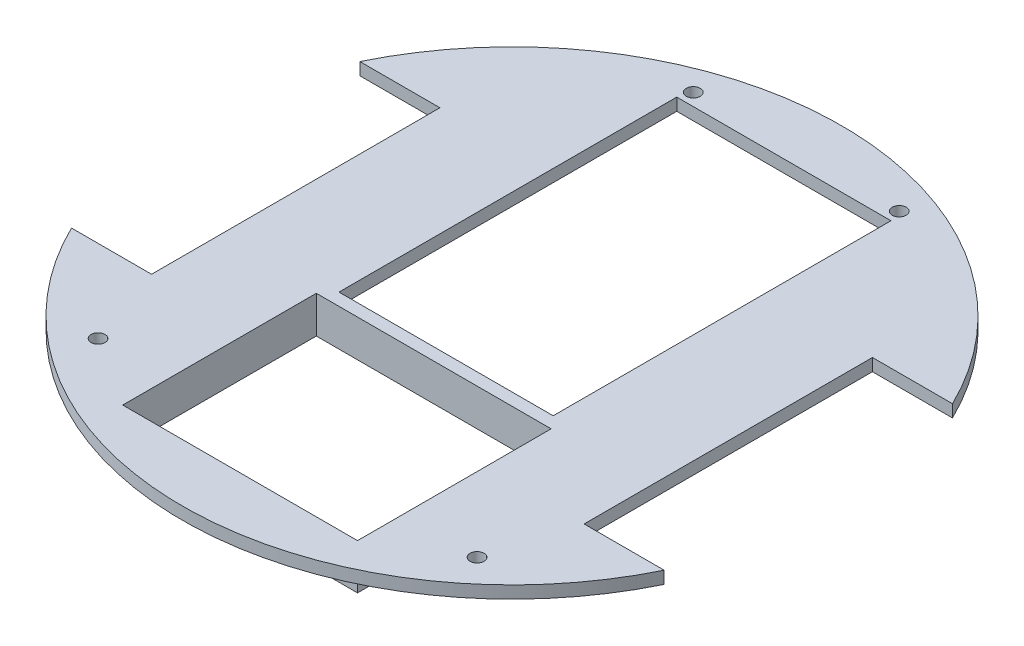
SolidWorks part; units mm, degrees
ref_plane "Plan de face" through (0, 0, 0) normal (0, 0, 1) x (1, 0, 0)
ref_plane "Plan de dessus" through (0, 0, 0) normal (0, 1, 0) x (1, 0, 0)
ref_plane "Plan de droite" through (0, 0, 0) normal (1, 0, 0) x (0, 0, -1)
sketch "Esquisse1" plane through (0, 0, 0) normal (0, 1, 0) x (1, 0, 0)
  circle A0 centre (0, 0) radius 80
  dimension "D1" = 160
extrude "Boss.-Extru.1" add sketch "Esquisse1" along normal blind 3
sketch "Esquisse2" plane through (0, 3, 0) normal (0, 1, 0) x (1, 0, 0)
  line L0 (0, -91.4679) -> (0, 85.097) construction
  line L1 (-107.5, -35) -> (-52.5, -35)
  line L2 (-107.5, -35) -> (-107.5, 35)
  line L3 (-107.5, 35) -> (-52.5, 35)
  line L4 (-52.5, -35) -> (-52.5, 35)
  line L5 (-107.5, -35) -> (-52.5, 35) construction
  line L6 (-107.5, 35) -> (-52.5, -35) construction
  line L7 (107.5, -35) -> (52.5, -35)
  line L8 (52.5, -35) -> (52.5, 35)
  line L9 (107.5, 35) -> (52.5, 35)
  line L10 (107.5, -35) -> (107.5, 35)
  circle A0 centre (0, 0) radius 80 construction
  point P0 (-80, 0)
  point P14 (0, 0)
  dimension "D1" = 70
  dimension "D2" = 55
extrude "Enlèv. mat.-Extru.1" cut sketch "Esquisse2" against normal through all
sketch "supports moteurs" plane through (0, 3, 0) normal (0, 1, 0) x (1, 0, 0)
  line L0 (-88.0211, 0) -> (120.7529, 0) construction
  line L1 (0, -36.8171) -> (0, 105.1916) construction
  line L2 (-48.5, -25) -> (-33.5, -25)
  line L3 (-48.5, -25) -> (-48.5, 65)
  line L4 (-48.5, 65) -> (-33.5, 65)
  line L5 (-33.5, -25) -> (-33.5, 65)
  line L6 (48.5, -25) -> (33.5, -25)
  line L7 (33.5, -25) -> (33.5, 65)
  line L8 (48.5, -25) -> (48.5, 65)
  line L9 (48.5, 65) -> (33.5, 65)
  line L10 (-52.5, -35) -> (-52.5, 35) construction
  dimension "D1" = 15
  dimension "D2" = 90
  dimension "D3" = 65
  dimension "D4" = 4
sketch "composants" plane through (0, 3, 0) normal (0, 1, 0) x (1, 0, 0)
  line L0 (0, -36.8171) -> (0, 105.1916) construction
  line L1 (-25, 65) -> (25, 65)
  line L2 (-25, 65) -> (-25, 15)
  line L3 (-25, 15) -> (25, 15)
  line L4 (25, 65) -> (25, 15)
  line L5 (13, 65) -> (13, 53) construction
  line L6 (-25, -15) -> (25, -15)
  line L7 (-25, -15) -> (-25, 10)
  line L8 (-25, 10) -> (25, 10)
  line L9 (25, -15) -> (25, 10)
  line L10 (-27.5, -20) -> (27.5, -20)
  line L11 (-27.5, -20) -> (-27.5, -65)
  line L12 (-27.5, -65) -> (27.5, -65)
  line L13 (27.5, -20) -> (27.5, -65)
  line L14 (13, 53) -> (25, 53) construction
  line L15 (-25, 27) -> (-13, 27) construction
  line L16 (-13, 27) -> (-13, 15) construction
  line L17 (-25, 10) -> (25, -15) construction
  line L18 (-25, -15) -> (25, 10) construction
  line L19 (25, -10) -> (10, -10) construction
  line L20 (10, -10) -> (10, -15) construction
  line L21 (-25, 5) -> (-10, 5) construction
  line L22 (-10, 5) -> (-10, 10) construction
  line L23 (-88.0211, 0) -> (120.7529, 0) construction
  point P4 (0, 65)
  point P15 (0, -20)
  point P28 (0, -2.5)
  dimension "D1" = 50
  dimension "D2" = 50
  dimension "D3" = 25
  dimension "D4" = 5
  dimension "D5" = 55
  dimension "D6" = 45
  dimension "D7" = 5
  dimension "D8" = 12
  dimension "D9" = 12
  dimension "D10" = 12
  dimension "D11" = 12
  dimension "D12" = 50
  dimension "D13" = 15
  dimension "D14" = 5
  dimension "D15" = 15
  dimension "D16" = 5
  dimension "D17" = 2.5
hole_wizard "Dégagement M31" positions "Esquisse10" profile "Esquisse9" hole size "M3" standard "Iso"
sketch "Esquisse10" plane through (0, 3, 0) normal (0, 1, 0) x (1, 0, 0)
  line L1 (-45.4836, -55) -> (0.5164, -55) construction
  line L2 (0.5164, -55) -> (46.5164, -55) construction
  line L6 (-25, 65) -> (25, 65) construction
  line L7 (-71.9375, -35) -> (-52.5, -35) construction
  point P4 (-45.4836, -55)
  point P6 (46.5164, -55)
  point P14 (-25, 69)
  point P16 (25, 69)
  dimension "D1" = 92
  dimension "D2" = 4
  dimension "D3" = 20
sketch "Esquisse9" plane through (-45.4836, 3, 55) normal (1, 0, 0) x (0, 0, 1)
  line L0 (0, 0) -> (0, 25.0215)
  line L1 (0, 25.0215) -> (1.7, 24)
  line L2 (1.7, 24) -> (1.7, 0)
  line L5 (1.7, 0) -> (0, 0)
  line L10 (0, 25.0215) -> (-1.7, 24) construction
  line L11 (0, -6.35) -> (0, 107.95) construction
  dimension "Diamètre du perçage" = 3.4
  dimension "Profondeur du perçage" = 24
  dimension "Angle de pointe" = 118
sketch "Esquisse11" plane through (0, 3, 0) normal (0, 1, 0) x (1, 0, 0)
  line L0 (-25, 65) -> (25, 65) construction
  line L1 (-26, 66) -> (26, 66)
  line L2 (-26, 66) -> (-26, -16)
  line L3 (-26, -16) -> (26, -16)
  line L4 (26, 66) -> (26, -16)
  line L5 (-25, 65) -> (-25, 15) construction
  line L6 (25, 65) -> (25, 15) construction
  line L7 (-25, -15) -> (25, -15) construction
  line L8 (-27.5, -20) -> (27.5, -20) construction
  line L9 (-28.5, -19) -> (28.5, -19)
  line L10 (-28.5, -19) -> (-28.5, -66)
  line L11 (-28.5, -66) -> (28.5, -66)
  line L12 (28.5, -19) -> (28.5, -66)
  line L13 (-27.5, -20) -> (-27.5, -65) construction
  line L14 (-27.5, -65) -> (27.5, -65) construction
  line L15 (27.5, -20) -> (27.5, -65) construction
  dimension "D1" = 1
  dimension "D2" = 1
  dimension "D3" = 1
  dimension "D4" = 1
  dimension "D5" = 1
  dimension "D6" = 1
  dimension "D7" = 1
  dimension "D8" = 1
extrude "Enlèv. mat.-Extru.2" cut sketch "Esquisse11" against normal through all
sketch "Esquisse12" plane through (0, 0, 0) normal (0, -1, 0) x (1, 0, 0)
  line L1 (-28.5, 66) -> (28.5, 66)
  line L2 (-28.5, 66) -> (-28.5, 19)
  line L3 (-28.5, 19) -> (28.5, 19)
  line L4 (28.5, 66) -> (28.5, 19)
  line L5 (-30.5, 68) -> (30.5, 68)
  line L6 (-30.5, 68) -> (-30.5, 17)
  line L7 (-30.5, 17) -> (30.5, 17)
  line L8 (30.5, 68) -> (30.5, 17)
  dimension "D1" = 2
  dimension "D2" = 2
  dimension "D3" = 2
  dimension "D4" = 2
extrude "Boss.-Extru.2" add sketch "Esquisse12" along normal blind 6
